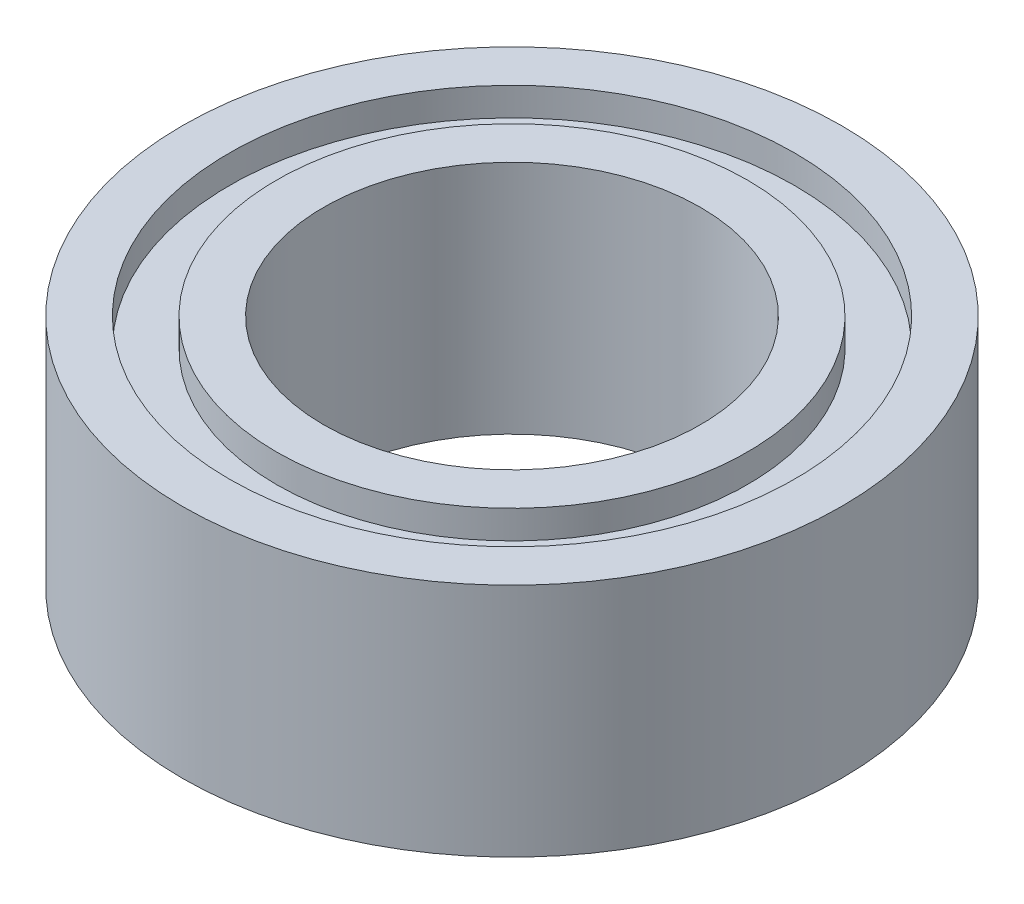
SolidWorks part; units mm, degrees
material "合金钢"
ref_plane "前视基准面" through (0, 0, 0) normal (0, 0, 1) x (1, 0, 0)
ref_plane "上视基准面" through (0, 0, 0) normal (0, 1, 0) x (1, 0, 0)
ref_plane "右视基准面" through (0, 0, 0) normal (1, 0, 0) x (0, 0, -1)
other "Configuration Table"
sketch "草图1" plane through (0, 0, 0) normal (0, 0, 1) x (1, 0, 0)
  line L0 (0, 7.969) -> (0, -6.8809) construction
  line L1 (2, 0) -> (2, 2.5)
  line L2 (2, 2.5) -> (2.5, 2.5)
  line L3 (2.5, 2.5) -> (2.5, 2.2)
  line L4 (2.5, 2.2) -> (3, 2.2)
  line L5 (3, 2.2) -> (3, 2.5)
  line L6 (3, 2.5) -> (3.5, 2.5)
  line L7 (3.5, 2.5) -> (3.5, 0)
  line L8 (3.5, 0) -> (3, 0)
  line L9 (3, 0) -> (3, 0.3)
  line L10 (3, 0.3) -> (2.5, 0.3)
  line L11 (2.5, 0.3) -> (2.5, 0)
  line L12 (2.5, 0) -> (2, 0)
  point P6 (0, 0)
  point P16 (0, 0)
  dimension "D1" = 2
  dimension "D2" = 3.5
  dimension "D3" = 3
  dimension "D4" = 2.5
  dimension "D5" = 0.3
  dimension "D6" = 0.3
  dimension "D7" = 2.5
  dimension "D8" = 2.5
revolve "旋转1" add sketch "草图1" angle 360 about L0
